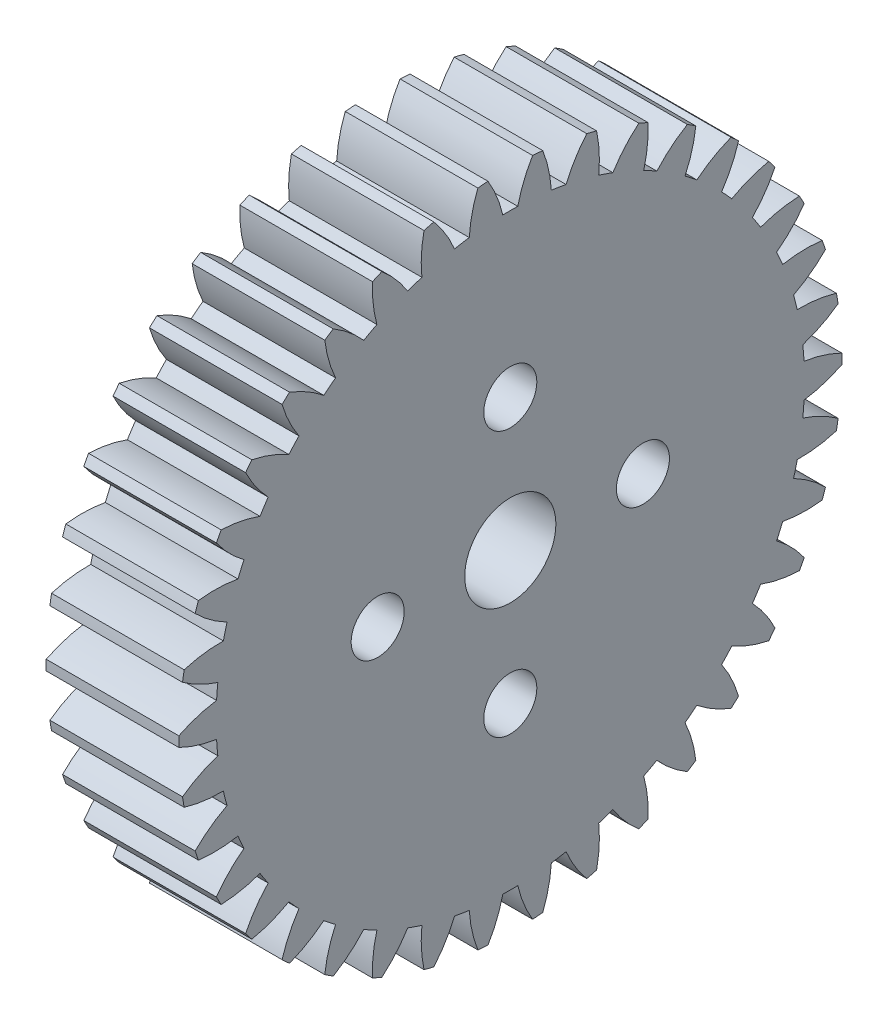
SolidWorks part; units mm, degrees
ref_plane "Plane1" through (0, 0, 0) normal (0, 0, 1) x (1, 0, 0)
ref_plane "Plane2" through (0, 0, 0) normal (0, 1, 0) x (1, 0, 0)
ref_plane "Plane3" through (0, 0, 0) normal (1, 0, 0) x (0, 0, -1)
other "Configuration Table"
sketch "HoldingSke" plane through (0, 0, 0) normal (0, 1, 0) x (1, 0, 0)
  line L0 (0, 0) -> (0.788, -0.6157)
  line L1 (-15, 0) -> (100, 0) construction
  line L2 (0, 0) -> (-2.1039, 2.3779)
  line L3 (0, 0) -> (-11.863, 4.5341)
  line L4 (0, 0) -> (6.8053, 5.3169)
  line L5 (0, 0) -> (-46.8476, -17.4728)
  line L6 (0, 0) -> (-8.2896, -5.593)
  line L7 (-2.1039, 2.3779) -> (8.6586, 51.2059)
  line L8 (-76.2, 54.61) -> (-76.1, 54.61)
  line L9 (-71.009, 38.7566) -> (-53.1078, 45.2721)
  line L10 (-76.2, 71.12) -> (104.1128, 71.12)
  line L11 (0, 0) -> (-10, 0)
  line L12 (-76.2, 101.6) -> (-76.162, 101.6)
  line L13 (24.9733, 27.94) -> (52.9518, 28.4284)
  line L14 (24.9733, 27.94) -> (24.9743, 27.94)
  line L15 (24.9733, 27.94) -> (100.4006, 29.5858)
  line L16 (-63.627, -1) -> (-12.827, -1)
  circle A0 centre (0, 0) radius 0.4
  circle A1 centre (0, 0) radius 17.749
  circle A2 centre (0, 0) radius 37.5
  circle A3 centre (0, 0) radius 0.4
  dimension "MHD" = 35.498
  dimension "Hub_dia" = 75
  dimension "Bore" = 0.8
  dimension "MBD" = 0.8
  dimension "Num_teeth" = 38
  dimension "Pitch" = 1
  dimension "Overall_len" = 50
  dimension "Show_teeth" = 38
  dimension "Thickness" = 10
  dimension "OAL" = 50.0001
  dimension "T_dim" = 0.1
  dimension "Ap" = 20
  dimension "H" = 19.05
  dimension "Pitch_radius" = 180.3128
  dimension "Width" = 10
  dimension "Backlash" = 0.038
  dimension "Addendum_fac" = 1
  dimension "Dedendum_fac" = 1.25
  dimension "Clearance_fac" = 0.25
  dimension "Dedendum_add" = 0.001
  dimension "Module" = 1
sketch "BasProSke" plane through (0, 0, 0) normal (0, 1, 0) x (1, 0, 0)
  line L0 (-10, 0) -> (60, 0) construction
  line L1 (0, 0) -> (0, 20)
  line L2 (0, 0) -> (10, 0)
  line L3 (10, 0) -> (10, 20)
  line L4 (10, 20) -> (0, 20)
  dimension "Thickness" = 10
  dimension "Diameter" = 40
revolve "Base-Revolve" add sketch "BasProSke" angle 360 about L0
sketch "TooCutSke" plane through (0, 0, 0) normal (1, 0, 0) x (0, 0, -1)
  line L1 (0, 0) -> (0, 107) construction
  line L2 (0, 0) -> (-0.8517, 18.9809) construction
  line L3 (0, 0) -> (-3.1358, 37.8431) construction
  line L4 (-0.8517, 18.9809) -> (-1.5679, 18.9216) construction
  arc A0 (0.4515, 17.7433) -> (-0.4515, 17.7433) centre (0, 0) ccw
  arc A1 (1.3614, 19.9791) -> (-1.3614, 19.9791) centre (0, 0) ccw
  circle A2 centre (0, 0) radius 19 construction
  circle A3 centre (0, 0) radius 17.8542 construction
  arc A4 (-0.4515, 17.7433) -> (-1.3614, 19.9791) centre (-7.8565, 16.0327) ccw
  arc A5 (1.3614, 19.9791) -> (0.4515, 17.7433) centre (7.8565, 16.0327) ccw
  dimension "Root_dia" = 35.498
  dimension "Overcut_dia" = 40.0508
  dimension "Pitch_dia" = 38
  dimension "Base_dia" = 35.7083
  dimension "Flank_rad" = 7.6
  dimension "Half_ang" = 4.737
  dimension "Half_CT" = 0.7187
extrude "ToothCut" cut sketch "TooCutSke" along normal through all
fillet "Breaks" [suppressed] radius 0.02
fillet "RootFillets" [suppressed] radius 0.251
pattern_circular "TeethCuts" count 38 every 9.474 about axis through (-10, 0, 0) along (1, 0, 0) of "ToothCut", "RootFillets", "Breaks"
sketch "HubNeaOneSke" plane through (0, 0, 0) normal (-1, 0, 0) x (0, 0, 1)
  circle A0 centre (0, 0) radius 17.749
  dimension "Diameter" = 35.498
extrude "HubNearOne" [suppressed] add sketch "HubNeaOneSke" along normal blind 40.0001
sketch "HubNeaBotSke" plane through (0, 0, 0) normal (-1, 0, 0) x (0, 0, 1)
  circle A0 centre (0, 0) radius 17.749
  dimension "Diameter" = 35.498
extrude "HubNearBoth" [suppressed] add sketch "HubNeaBotSke" along normal blind 20
ref_plane "FarPln" through (10, 0, 0) normal (1, 0, 0) x (0, 0, -1)
sketch "HubFarSke" plane through (10, 0, 0) normal (1, 0, 0) x (0, 0, -1)
  circle A0 centre (0, 0) radius 17.749
  dimension "Diameter" = 35.498
extrude "HubFar" [suppressed] add sketch "HubFarSke" along normal blind 20
sketch "BorSke" plane through (0, 0, 0) normal (1, 0, 0) x (0, 0, -1)
  circle A0 centre (0, 0) radius 0.4
  dimension "Diameter" = 0.8
extrude "Bore" cut sketch "BorSke" along normal mid plane 100.0001
sketch "KeySke" plane through (0, 0, 0) normal (1, 0, 0) x (0, 0, -1)
  line L0 (-0.05, 0) -> (-0.05, 0.5)
  line L1 (-0.05, 0.5) -> (0.05, 0.5)
  line L2 (0.05, 0.5) -> (0.05, 0)
  line L3 (0, 0) -> (0, 34) construction
  line L4 (-0.05, 0) -> (0.05, 0)
  dimension "Offset" = 0.5
  dimension "Width" = 0.1
extrude "Keyway" [suppressed] cut sketch "KeySke" along normal mid plane 100.0001
pattern_circular "Keyway2" [suppressed] count 2 every 90 about axis through (-10, 0, 0) along (1, 0, 0)
sketch "Sketch1" plane through (10, 0, 0) normal (1, 0, 0) x (0, 0, -1)
  circle A0 centre (0, 0) radius 2.75
  circle A1 centre (0, 8) radius 1.6
  circle A2 centre (8, 0) radius 1.6
  circle A3 centre (0, -8) radius 1.6
  circle A4 centre (-8, 0) radius 1.6
  point P13 (0, 0)
  dimension "D2" = 3.2
  dimension "D3" = 5.5
  dimension "D1" = 8
  dimension "D4" = 4
extrude "Cut-Extrude1" cut sketch "Sketch1" against normal through all
sketch "Sketch2" plane through (0, 0, 0) normal (-1, 0, 0) x (0, 0, 1)
  circle A0 centre (0, 0) radius 21.1606
extrude "Cut-Extrude2" cut sketch "Sketch2" against normal blind 2
equation "' \"Module@HoldingSke\" = 6.35"
equation "' \"Num_teeth@HoldingSke\" = 12"
equation "' \"Ap@HoldingSke\" =  20"
equation "' \"Ap@HoldingSke\" = 20"
equation "' \"Width@HoldingSke\" = 0.5 * 25.4"
equation "' \"Hub_dia@HoldingSke\"= 1 * 25.4"
equation "' \"Hub_dia@HoldingSke\" = 1 * 25.4"
equation "' \"Overall_len@HoldingSke\" = 1.0 * 25.4"
equation "' \"Bore@HoldingSke\" = 0.75 * 25.4"
equation "' \"T_dim@HoldingSke\" = 0.1 * 25.4"
equation "' \"Width@KeySke\" = 0.25 * 25.4"
equation "' \"Show_teeth@HoldingSke\" = 13"
equation "' \"Backlash@HoldingSke\" = 0.009 * 25.4"
equation "' \"Addendum_fac@HoldingSke\" = 1.0"
equation "' \"Dedendum_fac@HoldingSke\" = 1.25"
equation "' \"Dedendum_add@HoldingSke\" = 0.00005 * 25.4"
equation "' \"Clearance_fac@HoldingSke\" = 0.25"
equation "\"Pitch@HoldingSke\" = 1 / \"Module@HoldingSke\""
equation "\"Overcut_dia@TooCutSke\" = (\"Num_teeth@HoldingSke\" + 2 * \"Addendum_fac@HoldingSke\") / \"Pitch@HoldingSke\" + 0.002 * 25.4"
equation "\"Pitch_dia@TooCutSke\" = \"Num_teeth@HoldingSke\" / \"Pitch@HoldingSke\""
equation "\"Base_dia@TooCutSke\" = \"Num_teeth@HoldingSke\" / \"Pitch@HoldingSke\" * cos((\"Ap@HoldingSke\"  * 3.14159265 / 180))"
equation "\"Root_dia@TooCutSke\" = (\"Num_teeth@HoldingSke\" + 2) / \"Pitch@HoldingSke\" - 2 * (\"Addendum_fac@HoldingSke\" + \"Dedendum_fac@HoldingSke\") / \"Pitch@HoldingSke\" - \"Dedendum_add@HoldingSke\" * 2"
equation "\"Half_ang@TooCutSke\" = 180 / \"Num_teeth@HoldingSke\""
equation "\"Half_CT@TooCutSke\" = \"Num_teeth@HoldingSke\" / \"Pitch@HoldingSke\" * sin((3.14159265 / 2 / \"Num_teeth@HoldingSke\")) / 2 - 7 * \"Backlash@HoldingSke\" / 4"
equation "\"Flank_rad@TooCutSke\" = \"Num_teeth@HoldingSke\" / \"Pitch@HoldingSke\" / 5"
equation "\"Radius@RootFillets\" = \"Clearance_fac@HoldingSke\" / \"Pitch@HoldingSke\" + \"Dedendum_add@HoldingSke\""
equation "\"Break_rad@Breaks\" = 0.02 / \"Pitch@HoldingSke\""
equation "\"Thickness@HoldingSke\" = \"Width@HoldingSke\""
equation "\"OAL@HoldingSke\" = \"Thickness@HoldingSke\""
equation "\"MHD@HoldingSke\" = (\"Num_teeth@HoldingSke\" + 2) / \"Pitch@HoldingSke\" - 2 * (\"Addendum_fac@HoldingSke\" + \"Dedendum_fac@HoldingSke\")  / \"Pitch@HoldingSke\" - \"Dedendum_add@HoldingSke\" * 2"
equation "\"MBD@HoldingSke\" = (\"Num_teeth@HoldingSke\" + 2) / \"Pitch@HoldingSke\" - 2 * (\"Addendum_fac@HoldingSke\" + \"Dedendum_fac@HoldingSke\")  / \"Pitch@HoldingSke\" - \"Dedendum_add@HoldingSke\" * 2 - 0.002 * 25.4"
equation "\"MHD@HoldingSke\" = ((sgn( \"MHD@HoldingSke\" - \"Hub_dia@HoldingSke\" )-1)*( \"MHD@HoldingSke\" - \"Hub_dia@HoldingSke\" ))/-2+ \"Hub_dia@HoldingSke\""
equation "\"MBD@HoldingSke\" = ((sgn( \"MBD@HoldingSke\" - \"Bore@HoldingSke\" )-1)*( \"MBD@HoldingSke\" - \"Bore@HoldingSke\" ))/-2+ \"Bore@HoldingSke\""
equation "\"OAL@HoldingSke\" = ((sgn( \"OAL@HoldingSke\" - \"Overall_len@HoldingSke\" )+1)*( \"OAL@HoldingSke\" - \"Overall_len@HoldingSke\" ))/2 + \"Overall_len@HoldingSke\" + 0.000002 * 25.4"
equation "\"Num_teeth@TeethCuts\" = int( \"Show_teeth@HoldingSke\" ) + 1"
equation "\"Num_teeth@TeethCuts\" = ((sgn( \"Num_teeth@TeethCuts\" - \"Num_teeth@HoldingSke\" )-1)*( \"Num_teeth@TeethCuts\" - \"Num_teeth@HoldingSke\" ))/-2+ \"Num_teeth@HoldingSke\""
equation "\"Num_teeth@TeethCuts\" = ((sgn( \"Num_teeth@TeethCuts\" - 2.0)+1)*( \"Num_teeth@TeethCuts\" - 2.0))/2 +2.0"
equation "\"Angle@TeethCuts\" = 360.0 / \"Num_teeth@HoldingSke\""
equation "\"Diameter@BasProSke\" = (\"Num_teeth@HoldingSke\" + 2 * \"Addendum_fac@HoldingSke\") / \"Pitch@HoldingSke\""
equation "\"Thickness@BasProSke\"  = \"Thickness@HoldingSke\""
equation "' \"Fillet_rad@BasProSke\" =  \"Thickness@HoldingSke\" * 0.05"
equation "' \"Fillet_rad@BasProSke\" = \"Thickness@HoldingSke\" * 0.05"
equation "\"MHD@HoldingSke\" = ((sgn( \"MHD@HoldingSke\" - \"Root_dia@TooCutSke\" )-1)*( \"MHD@HoldingSke\" - \"Root_dia@TooCutSke\" ))/-2+ \"Root_dia@TooCutSke\""
equation "\"Diameter@HubNeaOneSke\" = \"MHD@HoldingSke\""
equation "\"Length@HubNearOne\" = \"OAL@HoldingSke\" - \"Thickness@BasProSke\""
equation "\"Diameter@HubNeaBotSke\" = \"MHD@HoldingSke\""
equation "\"Length@HubNearBoth\" = ( \"OAL@HoldingSke\" - \"Thickness@BasProSke\" ) / 2.0"
equation "\"Thickness@FarPln\" = \"Thickness@BasProSke\""
equation "\"Diameter@HubFarSke\" = \"MHD@HoldingSke\""
equation "\"Length@HubFar\" = ( \"OAL@HoldingSke\" - \"Thickness@BasProSke\" ) / 2.0"
equation "\"Diameter@BorSke\" = \"MBD@HoldingSke\""
equation "\"D1@Bore\" = \"OAL@HoldingSke\" * 2.0"
equation "\"D1@Keyway\" = \"OAL@HoldingSke\" * 2.0"
equation "\"Offset@KeySke\" = \"T_dim@HoldingSke\" + \"MBD@HoldingSke\" / 2.0"
